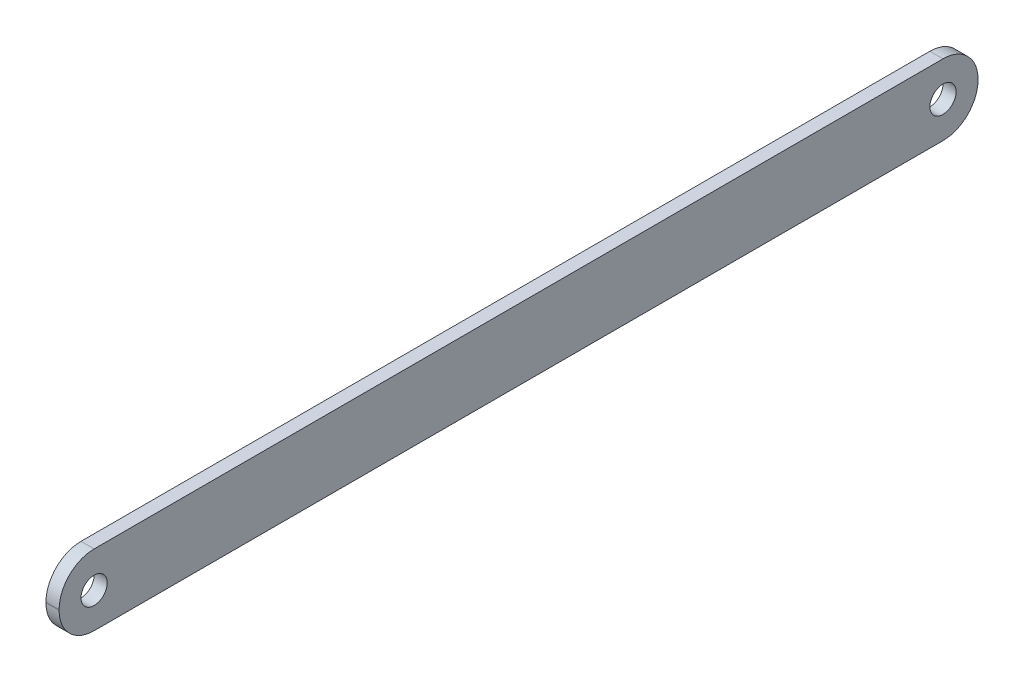
SolidWorks part; units mm, degrees
ref_plane "Front Plane" through (0, 0, 0) normal (0, 0, 1) x (1, 0, 0)
ref_plane "Top Plane" through (0, 0, 0) normal (0, 1, 0) x (1, 0, 0)
ref_plane "Right Plane" through (0, 0, 0) normal (1, 0, 0) x (0, 0, -1)
sketch "Sketch1" plane through (0, 0, 0) normal (1, 0, 0) x (0, 0, -1)
  line L1 (-97, 8.1) -> (97, 8.1)
  line L2 (-105, 0.1) -> (-105, -0.1)
  line L3 (-97, -8.1) -> (97, -8.1)
  line L4 (105, 0.1) -> (105, -0.1)
  line L5 (-105, 8.1) -> (105, -8.1) construction
  line L6 (-105, -8.1) -> (105, 8.1) construction
  arc A0 (97, 8.1) -> (105, 0.1) centre (97, 0.1) cw
  arc A1 (97, -8.1) -> (105, -0.1) centre (97, -0.1) ccw
  arc A2 (-105, -0.1) -> (-97, -8.1) centre (-97, -0.1) ccw
  arc A3 (-97, 8.1) -> (-105, 0.1) centre (-97, 0.1) ccw
  circle A4 centre (-97, -0.1) radius 3
  circle A5 centre (97, 0.1) radius 3
  point P0 (0, 0)
  dimension "D3" = 8
  dimension "D4" = 6
  dimension "D5" = 6
  dimension "D1" = 210
  dimension "D2" = 16.2
extrude "Boss-Extrude1" add sketch "Sketch1" along normal blind 3
